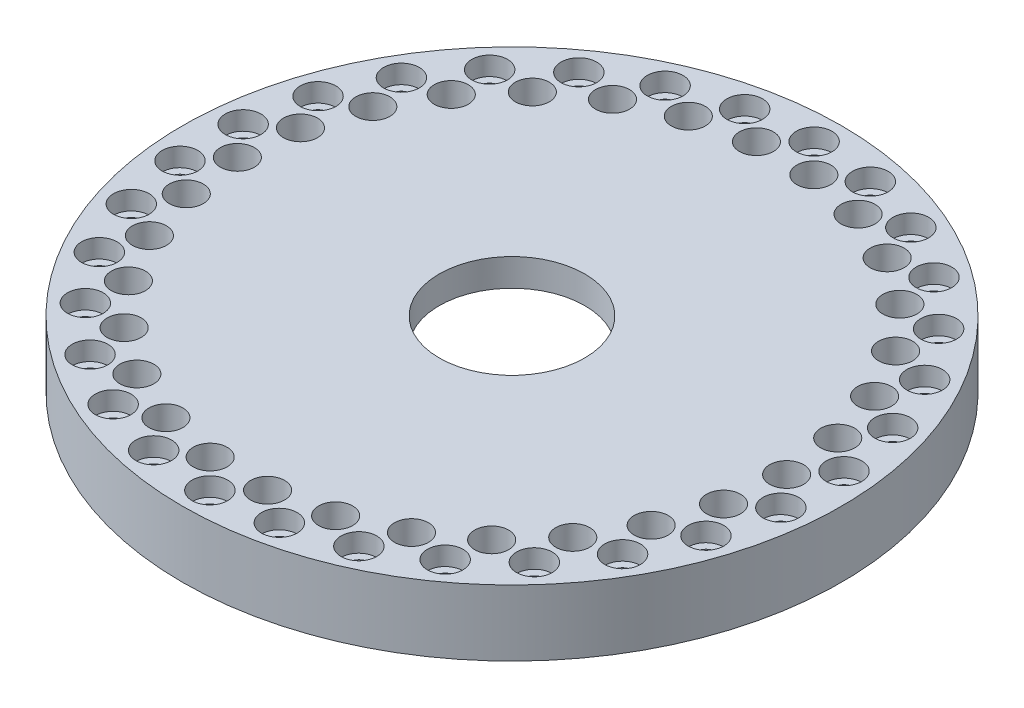
SolidWorks part; units mm, degrees
ref_plane "Front Plane" through (0, 0, 0) normal (0, 0, 1) x (1, 0, 0)
ref_plane "Top Plane" through (0, 0, 0) normal (0, 1, 0) x (1, 0, 0)
ref_plane "Right Plane" through (0, 0, 0) normal (1, 0, 0) x (0, 0, -1)
sketch "Sketch1" plane through (0, 0, 0) normal (0, 1, 0) x (1, 0, 0)
  circle A0 centre (0, 0) radius 60
  circle A3 centre (0, 0) radius 13.25
  dimension "D1" = 120
  dimension "D4" = 26.5
extrude "Boss-Extrude1" add sketch "Sketch1" along normal blind 12
hole_wizard "CBORE for M3 Hex Socket Head Cap Screw1" positions "Sketch2" profile "Sketch4" counterbore size "M3" standard "DIN" end condition through all
sketch "Sketch2" plane through (0, 12, 0) normal (0, 1, 0) x (1, 0, 0)
  point P0 (0, 55)
  point P8 (11.4351, 53.7981)
  point P9 (22.3705, 50.245)
  point P10 (32.3282, 44.4959)
  point P11 (40.873, 36.8022)
  point P12 (47.6314, 27.5)
  point P13 (52.3081, 16.9959)
  point P14 (54.6987, 5.7491)
  point P15 (54.6987, -5.7491)
  point P16 (52.3081, -16.9959)
  point P17 (47.6314, -27.5)
  point P18 (40.873, -36.8022)
  point P19 (32.3282, -44.4959)
  point P20 (22.3705, -50.245)
  point P21 (11.4351, -53.7981)
  point P22 (0, -55)
  point P23 (-11.4351, -53.7981)
  point P24 (-22.3705, -50.245)
  point P25 (-32.3282, -44.4959)
  point P26 (-40.873, -36.8022)
  point P27 (-47.6314, -27.5)
  point P28 (-52.3081, -16.9959)
  point P29 (-54.6987, -5.7491)
  point P30 (-54.6987, 5.7491)
  point P31 (-52.3081, 16.9959)
  point P32 (-47.6314, 27.5)
  point P33 (-40.873, 36.8022)
  point P34 (-32.3282, 44.4959)
  point P35 (-22.3705, 50.245)
  point P36 (-11.4351, 53.7981)
  dimension "D1" = 55
  dimension "D2" = 30
sketch "Sketch4" plane through (0, 12, -55) normal (1, 0, 0) x (0, 0, 1)
  line L0 (0, 0) -> (0, 12)
  line L1 (0, 12) -> (1.8, 12)
  line L3 (1.8, 12) -> (1.8, 3.4)
  line L4 (1.8, 3.4) -> (3.25, 3.4)
  line L5 (3.25, 3.4) -> (3.25, 0)
  line L7 (3.25, 0) -> (0, 0)
  line L11 (0, -6.35) -> (0, 107.95) construction
  dimension "Thru Hole Dia." = 3.6
  dimension "Thru Hole Depth" = 12
  dimension "C'Bore Dia." = 6.5
  dimension "C'Bore Depth" = 3.4
hole_wizard "Ø6.2 (6.2) Diameter Hole1" positions "Sketch5" profile "Sketch6" hole size "Ø6.2" standard "DIN" end condition through all
sketch "Sketch5" plane through (0, 0, 0) normal (0, -1, 0) x (-1, 0, 0)
  line L0 (-11.4351, 53.7981) -> (0, 55) construction
  line L2 (-5.7176, 54.3991) -> (0, 0) construction
  circle A0 centre (0, 0) radius 50 construction
  point P6 (-5.2264, 49.7261)
  point P23 (5.2264, 49.7261)
  point P24 (15.4508, 47.5528)
  point P25 (25, 43.3013)
  point P26 (33.4565, 37.1572)
  point P27 (40.4508, 29.3893)
  point P28 (45.6773, 20.3368)
  point P29 (48.9074, 10.3956)
  point P30 (50, 0)
  point P31 (48.9074, -10.3956)
  point P32 (45.6773, -20.3368)
  point P33 (40.4508, -29.3893)
  point P34 (33.4565, -37.1572)
  point P35 (25, -43.3013)
  point P36 (15.4508, -47.5528)
  point P37 (5.2264, -49.7261)
  point P38 (-5.2264, -49.7261)
  point P39 (-15.4508, -47.5528)
  point P40 (-25, -43.3013)
  point P41 (-33.4565, -37.1572)
  point P42 (-40.4508, -29.3893)
  point P43 (-45.6773, -20.3368)
  point P44 (-48.9074, -10.3956)
  point P45 (-50, 0)
  point P46 (-48.9074, 10.3956)
  point P47 (-45.6773, 20.3368)
  point P48 (-40.4508, 29.3893)
  point P49 (-33.4565, 37.1572)
  point P50 (-25, 43.3013)
  point P51 (-15.4508, 47.5528)
  dimension "D1" = 100
  dimension "D2" = 30
sketch "Sketch6" plane through (15.4508, 0, -47.5528) normal (1, 0, 0) x (0, 0, -1)
  line L0 (0, 0) -> (0, 12)
  line L1 (0, 12) -> (3.1, 12)
  line L2 (3.1, 12) -> (3.1, 0)
  line L5 (3.1, 0) -> (0, 0)
  line L11 (0, -6.35) -> (0, 107.95) construction
  dimension "Thru Hole Dia." = 6.2
  dimension "Thru Hole Depth" = 12
sketch "Sketch7" plane through (0, 0, 0) normal (0, -1, 0) x (1, 0, 0)
  circle A0 centre (0, 0) radius 23.5
  dimension "D1" = 47
extrude "Cut-Extrude1" cut sketch "Sketch7" against normal blind 7
sketch "Sketch8" plane through (0, 7, 0) normal (0, -1, 0) x (1, 0, 0)
  circle A4 centre (0, 0) radius 23.5 construction
  circle A5 centre (0, 0) radius 19.5
  circle A6 centre (0, 0) radius 19.5
  circle A7 centre (0, 0) radius 23.5
  dimension "D1" = 4
extrude "Boss-Extrude2" add sketch "Sketch8" along normal blind 0.6
sketch "Sketch9" plane through (0, 0, 0) normal (0, 0, 1) x (1, 0, 0)
  line L0 (-23.5, 6.4) -> (23.5, 6.4) construction
  circle A0 centre (-23.5, 6.4) radius 0.75
  dimension "D1" = 1.5
ref_axis "Axis1" through (0, 12, 0) along (0, -1, 0)
revolve "Cut-Revolve1" cut sketch "Sketch9" angle 360 about axis through (0, 12, 0) along (0, -1, 0)
sketch "Sketch10" plane through (0, 0, 0) normal (0, 0, 1) x (1, 0, 0)
  line L0 (-46.9, 0) -> (-46.9, 1)
  line L1 (-53.1, 0) -> (-46.9, 0) construction
  line L2 (-52.0074, 0) -> (-45.8074, 0) construction
  line L3 (-46.9, 1) -> (-45.9, 0)
  line L4 (-48.7773, 0) -> (-42.5773, 0) construction
  line L5 (-45.9, 0) -> (-46.9, 0)
  dimension "D1" = 1
ref_axis "Axis2" through (-50, 12, 0) along (0, -1, 0)
revolve "Cut-Revolve2" cut sketch "Sketch10" angle 360 about axis through (-50, 12, 0) along (0, -1, 0)
pattern_circular "CirPattern2" count 30 over 360 about axis through (0, 0, 0) along (0, 1, 0) of "Cut-Revolve2"
